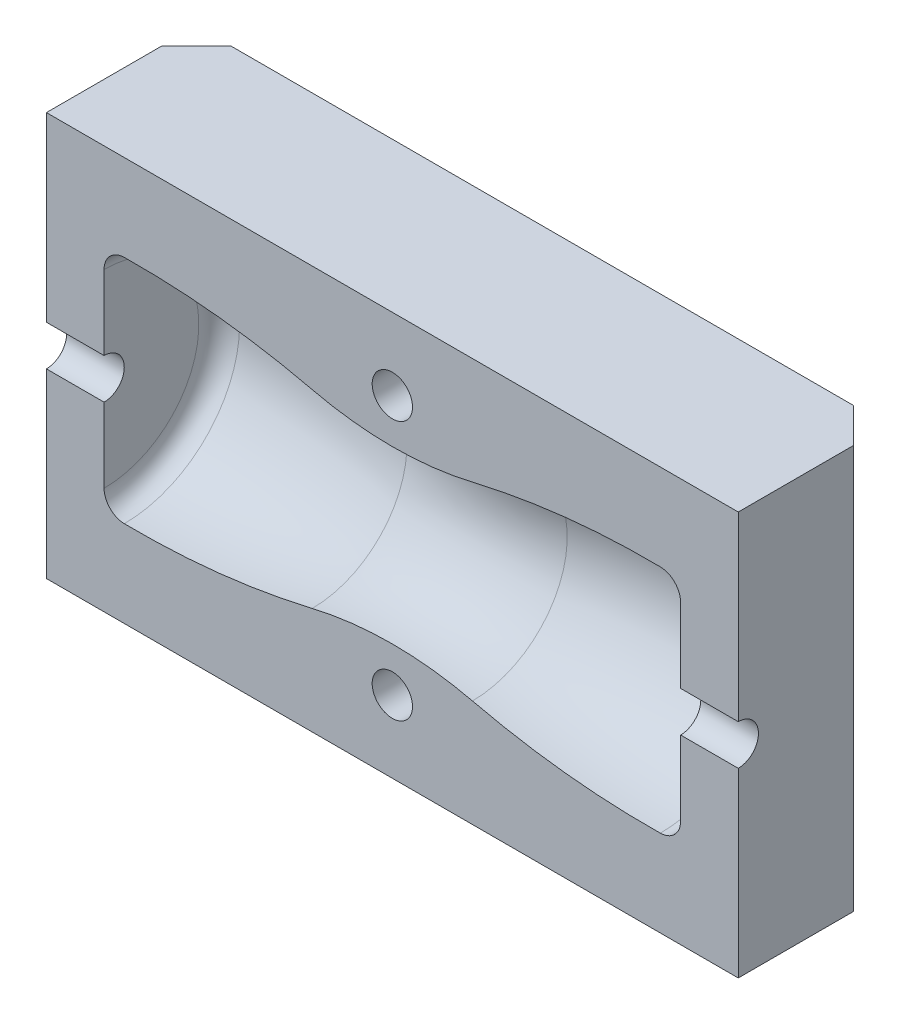
SolidWorks part; units mm, degrees
ref_plane "Front Plane" through (0, 0, 0) normal (0, 0, 1) x (1, 0, 0)
ref_plane "Top Plane" through (0, 0, 0) normal (0, 1, 0) x (1, 0, 0)
ref_plane "Right Plane" through (0, 0, 0) normal (1, 0, 0) x (0, 0, -1)
sketch "Sketch1" plane through (0, 0, 0) normal (0, 0, 1) x (1, 0, 0)
  line L1 (-30, 17.5) -> (30, 17.5)
  line L2 (-30, 17.5) -> (-30, -17.5)
  line L3 (-30, -17.5) -> (30, -17.5)
  line L4 (30, 17.5) -> (30, -17.5)
  line L5 (-30, 17.5) -> (30, -17.5) construction
  line L6 (-30, -17.5) -> (30, 17.5) construction
  point P0 (0, 0)
  dimension "D1" = 35
  dimension "D2" = 60
extrude "Boss-Extrude1" add sketch "Sketch1" along normal blind 13
sketch "Sketch2" plane through (0, 0, 13) normal (0, 0, 1) x (1, 0, 0)
  line L0 (-30, 0) -> (30, 0) construction
  line L1 (-30, 17.5) -> (-30, -17.5) construction
  line L2 (30, -17.5) -> (30, 17.5) construction
  line L3 (-25, 0) -> (-25, 8.2181)
  line L4 (-6.9483, 8.2181) -> (6.9483, 8.2181) construction
  line L5 (0, 8.2181) -> (0, 0) construction
  line L6 (25, 8.2181) -> (25, 0)
  line L7 (25, 0) -> (-25, 0)
  line L8 (-25, 8.2181) -> (25, 8.2181) construction
  line L9 (23.2433, 10) -> (-23.2433, 10) construction
  arc A0 (-25, 8.2181) -> (-23.2433, 10) centre (-23.2179, 8.2181) cw
  arc A1 (-23.2433, 10) -> (-6.9483, 8.2181) centre (-22.2956, -56.7322) cw
  arc A2 (-6.9483, 8.2181) -> (6.9483, 8.2181) centre (0, 37.6237) ccw
  arc A3 (6.9483, 8.2181) -> (23.2433, 10) centre (22.2956, -56.7322) cw
  arc A4 (23.2433, 10) -> (25, 8.2181) centre (23.2179, 8.2181) cw
  dimension "D3" = 1.7821
  dimension "D1" = 50
  dimension "D2" = 10
revolve "Cut-Revolve1" cut sketch "Sketch2" angle 360 about L7
sketch "Sketch3" plane through (30, 0, 0) normal (1, 0, 0) x (0, 0, -1)
  line L0 (-13, -17.5) -> (-13, 17.5) construction
  circle A0 centre (-13, 0) radius 1.75
  dimension "D1" = 3.5
extrude "Cut-Extrude1" cut sketch "Sketch3" against normal through all both
sketch "Sketch5" plane through (0, 0, 13) normal (0, 0, 1) x (1, 0, 0)
  line L0 (0, 11.25) -> (0, -11.25) construction
  circle A0 centre (0, 11.25) radius 1.75
  circle A1 centre (0, -11.25) radius 1.75
  dimension "D1" = 3.5
  dimension "D2" = 22.5
extrude "Cut-Extrude3" cut sketch "Sketch5" against normal through all
chamfer "Chamfer1" distance 3 angle 45 2 edges at (30, 0, 0) (-30, 0, 0)
sketch "Sketch6" plane through (0, 0, 0) normal (0, 0, -1) x (-1, 0, 0)
  line L1 (3.4641, 11.25) -> (1.7321, 14.25)
  line L2 (1.7321, 14.25) -> (-1.7321, 14.25)
  line L3 (-1.7321, 14.25) -> (-3.4641, 11.25)
  line L4 (-3.4641, 11.25) -> (-1.7321, 8.25)
  line L5 (-1.7321, 8.25) -> (1.7321, 8.25)
  line L6 (1.7321, 8.25) -> (3.4641, 11.25)
  line L7 (3.4641, -11.25) -> (1.7321, -8.25)
  line L8 (1.7321, -8.25) -> (-1.7321, -8.25)
  line L9 (-1.7321, -8.25) -> (-3.4641, -11.25)
  line L10 (-3.4641, -11.25) -> (-1.7321, -14.25)
  line L11 (-1.7321, -14.25) -> (1.7321, -14.25)
  line L12 (1.7321, -14.25) -> (3.4641, -11.25)
  circle A0 centre (0, 11.25) radius 3 construction
  circle A1 centre (0, -11.25) radius 3 construction
  dimension "D1" = 6
extrude "Cut-Extrude4" cut sketch "Sketch6" against normal blind 7
chamfer "Chamfer2" distance 0.5 angle 45 26 edges at (-2.5981, -9.75, 0) (-2.5981, 12.75, 0) (-1.75, 11.25, 7) (0, 8.25, 7) (2.5981, 9.75, 7) (2.5981, 12.75, 7) (0, 14.25, 7) (-2.5981, 12.75, 7) (-2.5981, 9.75, 7) (-1.75, -11.25, 7) (0, -14.25, 7) (2.5981, -12.75, 7) (2.5981, -9.75, 7) (0, -8.25, 7) (-2.5981, -9.75, 7) (-2.5981, -12.75, 7) (-2.5981, -12.75, 0) (0, -14.25, 0) (2.5981, -12.75, 0) (2.5981, -9.75, 0) (0, -8.25, 0) (-2.5981, 9.75, 0) (0, 8.25, 0) (2.5981, 9.75, 0) (2.5981, 12.75, 0) (0, 14.25, 0)
